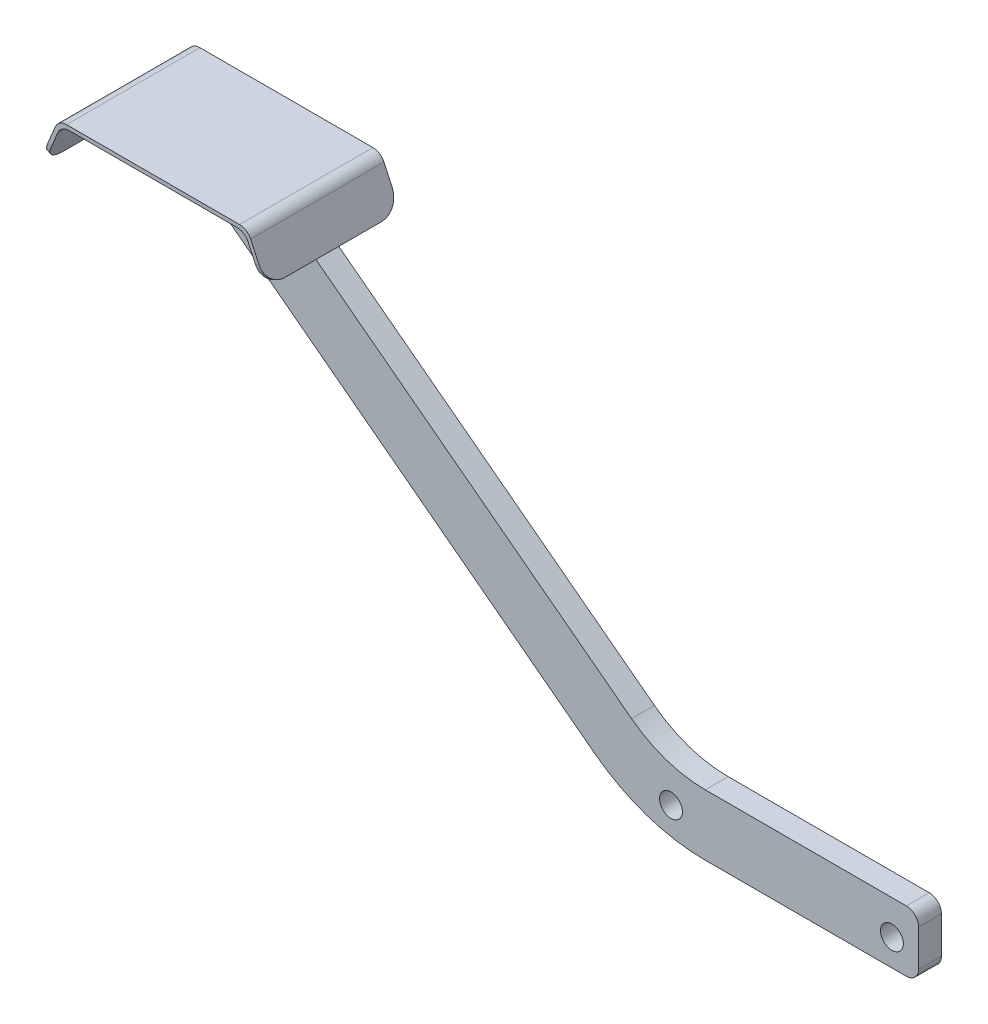
SolidWorks part; units mm, degrees
material "Alloy Steel"
ref_plane "Front Plane" through (0, 0, 0) normal (0, 0, 1) x (1, 0, 0)
ref_plane "Top Plane" through (0, 0, 0) normal (0, 1, 0) x (1, 0, 0)
ref_plane "Right Plane" through (0, 0, 0) normal (1, 0, 0) x (0, 0, -1)
other "Configuration Table"
sketch "Sketch1" plane through (0, 0, 0) normal (0, 0, 1) x (1, 0, 0)
  line L0 (126.3839, 0) -> (37.4839, 0)
  line L1 (55, 0) -> (-55, 0) construction
  line L2 (-8.6081, 15.5208) -> (-190.6458, 153.7967)
  line L3 (126.3839, 25.4) -> (37.4839, 25.4)
  line L4 (6.7559, 35.7472) -> (-148.6541, 153.7967)
  line L5 (-190.6458, 153.7967) -> (-148.6541, 153.7967)
  line L6 (126.3839, 25.4) -> (126.3839, 0)
  line L7 (6.7559, 35.7472) -> (-175.2818, 174.0231) construction
  arc A0 (37.4839, 0) -> (-8.6081, 15.5208) centre (37.4839, 76.2) cw
  arc A1 (37.4839, 25.4) -> (6.7559, 35.7472) centre (37.4839, 76.2) cw
  dimension "D3" = 76.2
  dimension "D1" = 88.9
  dimension "D2" = 228.6
  dimension "D4" = 25.4
extrude "Boss-Extrude1" add sketch "Sketch1" against normal blind 9.525
fillet "Fillet1" radius 5.08 2 edges at (126.3839, 0, -4.7625) (126.3839, 25.4, -4.7625)
sketch "Sketch2" plane through (0, 0, 0) normal (0, 0, 1) x (1, 0, 0)
  line L0 (126.3839, 5.08) -> (126.3839, 20.32) construction
  line L1 (37.4839, 0) -> (121.3039, 0) construction
  circle A0 centre (115.2714, 11.1125) radius 4.7625
  circle A1 centre (23.1964, 12.7) radius 4.7625
  dimension "D1" = 9.525
  dimension "D2" = 11.1125
  dimension "D3" = 11.1125
  dimension "D4" = 92.075
  dimension "D5" = 12.7
extrude "Cut-Extrude1" cut sketch "Sketch2" against normal through all
ref_plane "Plane1" through (0, 0, -4.7625) normal (0, 0, 1) x (1, 0, 0)
sketch "Sketch3" plane through (0, 0, -4.7625) normal (0, 0, 1) x (1, 0, 0)
  line L0 (-190.6458, 153.7967) -> (-148.6541, 153.7967)
  line L1 (-131.3196, 153.7967) -> (-123.7476, 137.428)
  line L2 (-190.6458, 153.7967) -> (-207.9803, 153.7967)
  line L3 (-148.6541, 153.7967) -> (-131.3196, 153.7967)
  line L4 (-207.9803, 153.7967) -> (-214.9155, 137.1943)
  line L5 (-209.0376, 155.3842) -> (-216.3803, 137.8062)
  line L6 (-190.6458, 155.3842) -> (-209.0376, 155.3842)
  line L7 (-190.6458, 155.3842) -> (-148.6541, 155.3842)
  line L8 (-148.6541, 155.3842) -> (-130.3048, 155.3842)
  line L9 (-130.3048, 155.3842) -> (-122.3068, 138.0945)
  line L10 (-216.3803, 137.8062) -> (-214.9155, 137.1943)
  line L11 (-123.7476, 137.428) -> (-122.3068, 138.0945)
  dimension "D2" = 19.05
  dimension "D3" = 19.05
  dimension "D4" = 94.0736
  dimension "D1" = 1.5875
extrude "Boss-Extrude2" add sketch "Sketch3" along normal mid plane 55.5625
fillet "Fillet2" radius 5.08 4 edges at (-209.0376, 155.3842, -4.7625) (-207.9803, 153.7967, -4.7625) (-131.3196, 153.7967, -4.7625) (-130.3048, 155.3842, -4.7625)
fillet "Fillet3" radius 7.62 4 edges at (-215.6479, 137.5003, -32.5438) (-123.0272, 137.7613, -32.5438) (-123.0272, 137.7613, 23.0187) (-215.6479, 137.5003, 23.0187)
